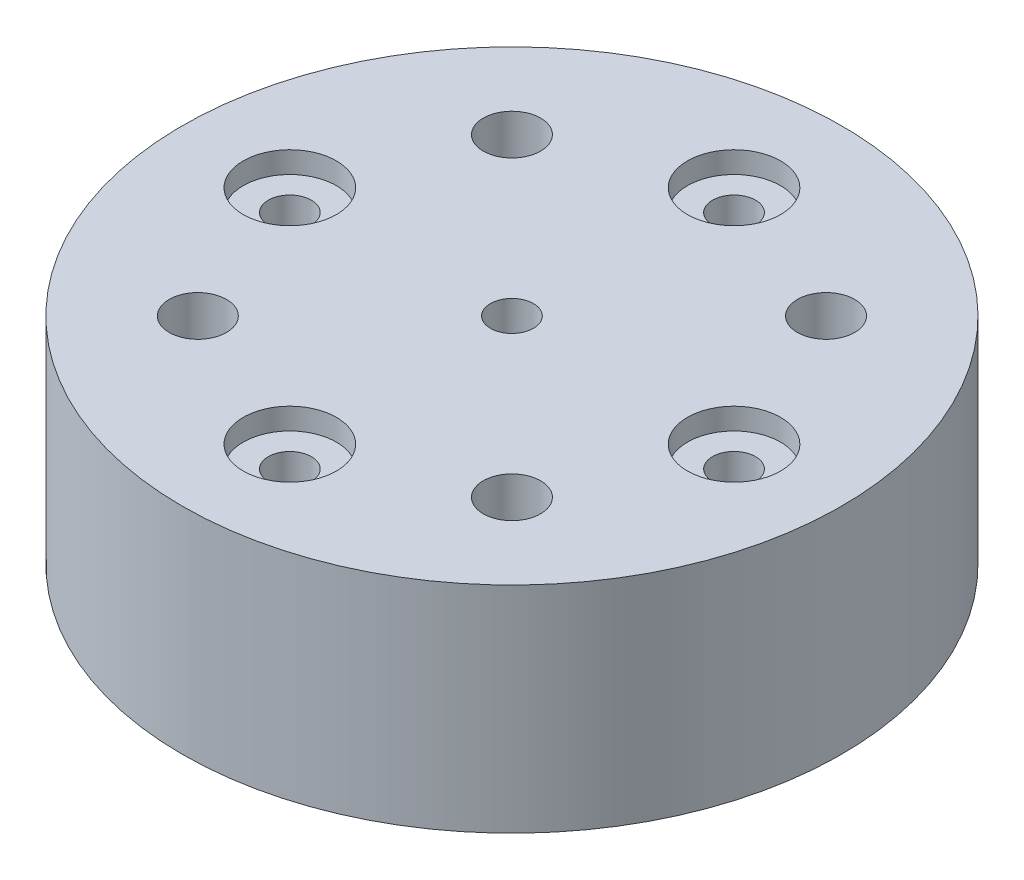
SolidWorks part; units mm, degrees
ref_plane "Front Plane" through (0, 0, 0) normal (0, 0, 1) x (1, 0, 0)
ref_plane "Top Plane" through (0, 0, 0) normal (0, 1, 0) x (1, 0, 0)
ref_plane "Right Plane" through (0, 0, 0) normal (1, 0, 0) x (0, 0, -1)
sketch "Sketch1" plane through (0, 0, 0) normal (0, 1, 0) x (1, 0, 0)
  circle A0 centre (0, 0) radius 15.5 construction
  circle A1 centre (0, 15.5) radius 1.5
  circle A2 centre (15.5, 0) radius 1.5
  circle A3 centre (0, -15.5) radius 1.5
  circle A4 centre (-15.5, 0) radius 1.5
  circle A5 centre (0, 0) radius 23
  circle A6 centre (0, 0) radius 4 construction
  circle A9 centre (0, 0) radius 1.5
  point P14 (0, 0)
  dimension "D1" = 31
  dimension "D2" = 3
  dimension "D4" = 46
  dimension "D5" = 8
  dimension "D7" = 3
  dimension "D3" = 4
extrude "Boss-Extrude1" add sketch "Sketch1" along normal blind 15
sketch "Sketch2" plane through (0, 15, 0) normal (0, 1, 0) x (1, 0, 0)
  circle A0 centre (0, 0) radius 15.5 construction
  circle A1 centre (0, 15.5) radius 3.25
  circle A2 centre (15.5, 0) radius 3.25
  circle A3 centre (0, -15.5) radius 3.25
  circle A4 centre (-15.5, 0) radius 3.25
  point P15 (0, 0)
  dimension "D1" = 6.5
  dimension "D2" = 4
extrude "Cut-Extrude1" cut sketch "Sketch2" against normal blind 1.5
sketch "Sketch3" plane through (0, 15, 0) normal (0, 1, 0) x (1, 0, 0)
  line L0 (-10.9602, 10.9602) -> (0, 0) construction
  line L1 (0, 0) -> (7.4736, 0) construction
  circle A0 centre (0, 0) radius 15.5 construction
  circle A1 centre (-10.9602, 10.9602) radius 2
  circle A2 centre (10.9602, 10.9602) radius 2
  circle A3 centre (10.9602, -10.9602) radius 2
  circle A4 centre (-10.9602, -10.9602) radius 2
  point P16 (0, 0)
  dimension "D1" = 4
  dimension "D2" = 135
  dimension "D3" = 4
extrude "Cut-Extrude2" cut sketch "Sketch3" against normal blind 10
